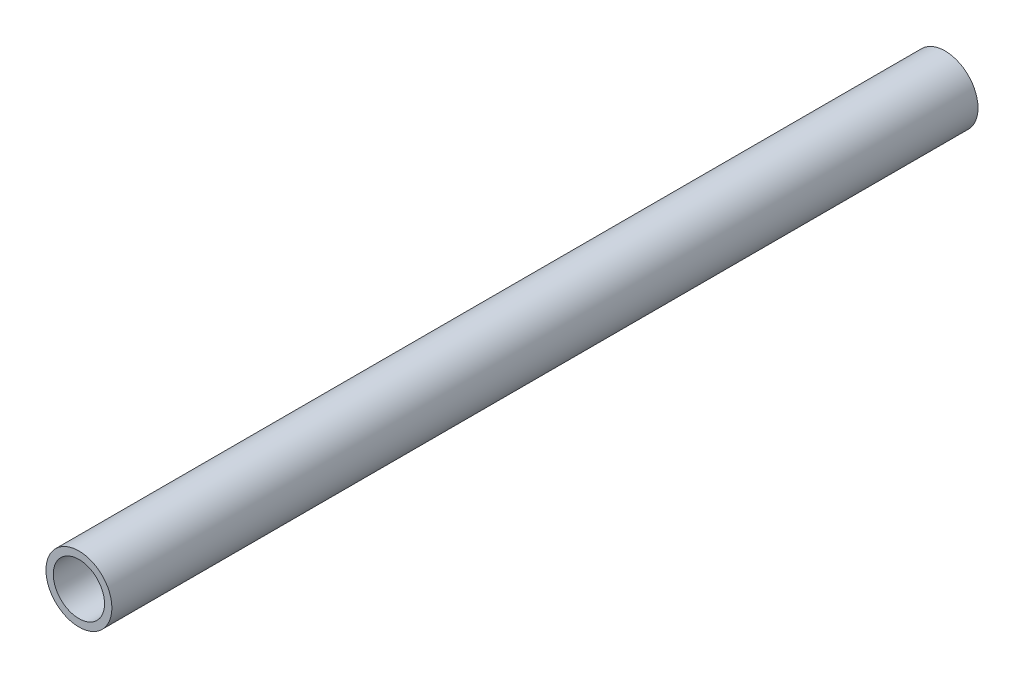
SolidWorks part; units mm, degrees
ref_plane "前视基准面" through (0, 0, 0) normal (0, 0, 1) x (1, 0, 0)
ref_plane "上视基准面" through (0, 0, 0) normal (0, 1, 0) x (1, 0, 0)
ref_plane "右视基准面" through (0, 0, 0) normal (1, 0, 0) x (0, 0, -1)
other "Configuration Table"
sketch "草图1" plane through (0, 0, 0) normal (0, 0, 1) x (1, 0, 0)
  circle A0 centre (0, 0) radius 7
  circle A1 centre (0, 0) radius 9
  dimension "D1" = 14
  dimension "D2" = 18
extrude "凸台-拉伸1" add sketch "草图1" along normal blind 236.4
